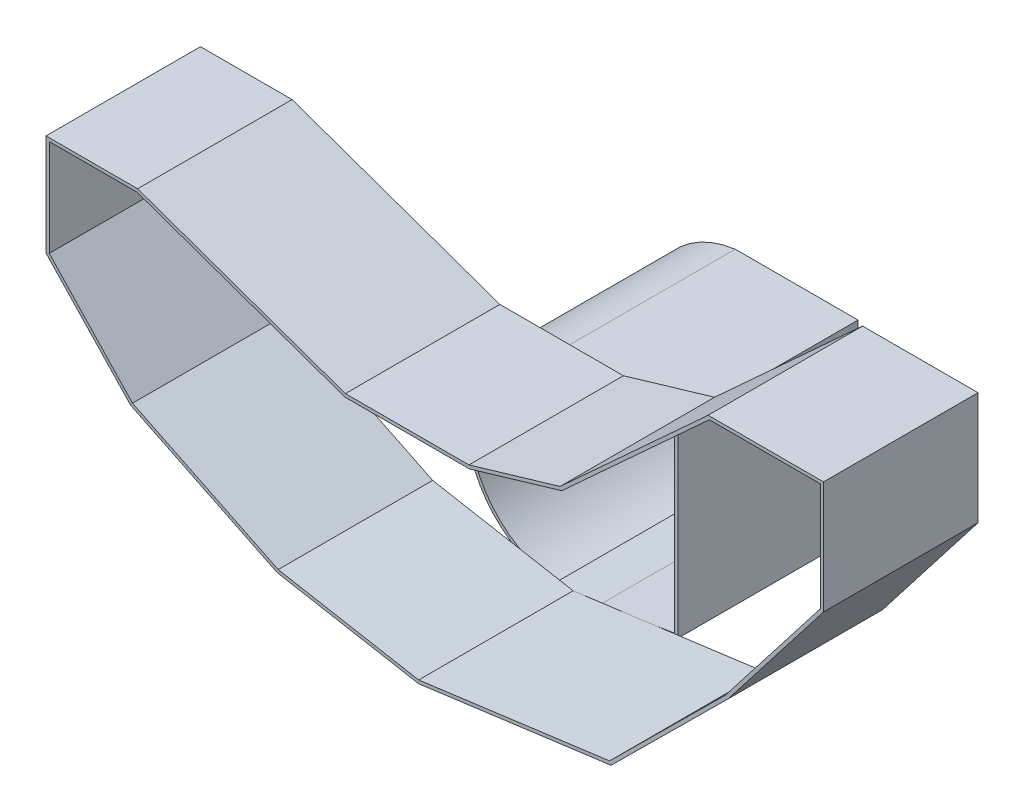
SolidWorks part; units mm, degrees
ref_plane "Front Plane" through (0, 0, 0) normal (0, 0, 1) x (1, 0, 0)
ref_plane "Top Plane" through (0, 0, 0) normal (0, 1, 0) x (1, 0, 0)
ref_plane "Right Plane" through (0, 0, 0) normal (1, 0, 0) x (0, 0, -1)
sketch "Sketch1" plane through (0, 0, 0) normal (0, 0, 1) x (1, 0, 0)
  line L0 (0, 0) -> (0, -75.438)
  line L1 (0, -75.438) -> (149.098, -55.626)
  line L2 (149.098, -55.626) -> (239.776, 34.29)
  line L3 (239.776, 34.29) -> (313.69, 129.54)
  line L4 (313.69, 129.54) -> (313.69, 214.122)
  line L5 (313.69, 214.122) -> (227.076, 214.122)
  line L10 (-219.964, 144.526) -> (-288.544, 144.526)
  line L11 (-288.544, 144.526) -> (-288.544, 68.834)
  line L12 (-288.544, 68.834) -> (-223.52, 0)
  line L15 (-223.52, 0) -> (-109.728, -55.626)
  line L16 (-109.728, -55.626) -> (0, -75.438)
  line L17 (-219.964, 144.526) -> (-57.658, 87.122)
  line L18 (-57.658, 87.122) -> (39.624, 87.122)
  line L20 (111.76, 108.458) -> (227.076, 214.122)
  line L22 (-219.5281, 147.066) -> (-57.2221, 89.662)
  line L23 (-57.2221, 89.662) -> (39.2562, 89.662)
  line L24 (39.2562, 89.662) -> (110.4768, 110.7272)
  line L25 (110.4768, 110.7272) -> (226.0883, 216.662)
  line L26 (226.0883, 216.662) -> (316.23, 216.662)
  line L27 (316.23, 216.662) -> (316.23, 128.6701)
  line L28 (316.23, 128.6701) -> (241.6816, 32.6025)
  line L29 (241.6816, 32.6025) -> (150.2797, -58.0313)
  line L30 (150.2797, -58.0313) -> (-0.0598, -78.0083)
  line L31 (-0.0598, -78.0083) -> (-110.5265, -58.0629)
  line L32 (-110.5265, -58.0629) -> (-225.0498, -2.0794)
  line L33 (-225.0498, -2.0794) -> (-291.084, 67.824)
  line L34 (-291.084, 67.824) -> (-291.084, 147.066)
  line L35 (-291.084, 147.066) -> (-219.5281, 147.066)
  line L36 (111.76, 108.458) -> (39.624, 87.122)
  point P3 (-223.52, 0)
  point P4 (-109.728, -55.626)
  point P5 (-288.544, 68.834)
  point P6 (149.098, -55.626)
  point P7 (239.776, 34.29)
  point P8 (313.69, 129.54)
  point P9 (313.69, 214.122)
  point P10 (-288.544, 144.526)
  point P11 (-219.964, 144.526)
  point P12 (-155.194, 113.792)
  point P13 (-57.658, 87.122)
  point P14 (39.624, 87.122)
  point P15 (111.76, 108.458)
  point P16 (227.076, 214.122)
  dimension "D1" = 75.438
  dimension "D2" = 149.098
  dimension "D3" = 19.812
  dimension "D4" = 109.728
  dimension "D5" = 223.52
  dimension "D6" = 75.438
  dimension "D7" = 602.234
  dimension "D8" = 144.272
  dimension "D9" = 239.776
  dimension "D10" = 109.728
  dimension "D11" = 313.69
  dimension "D12" = 204.978
  dimension "D13" = 289.56
  dimension "D14" = 219.964
  dimension "D15" = 68.58
  dimension "D16" = 133.35
  dimension "D17" = 189.23
  dimension "D18" = 230.886
  dimension "D19" = 162.56
  dimension "D21" = 328.168
  dimension "D22" = 400.304
  dimension "D23" = 515.62
  dimension "D24" = 19.812
  dimension "D25" = 183.896
  dimension "D26" = 2.54
  dimension "D27" = 2.54
  dimension "D28" = 2.54
  dimension "D29" = 2.54
  dimension "D30" = 2.54
  dimension "D31" = 2.54
  dimension "D32" = 2.54
  dimension "D33" = 2.54
  dimension "D34" = 2.54
  dimension "D35" = 2.54
  dimension "D36" = 2.54
  dimension "D37" = 2.54
  dimension "D38" = 2.54
  dimension "D39" = 2.54
extrude "Boss-Extrude1" add sketch "Sketch1" against normal blind 120.65 contours L35 L34 L33 L32 L31 L30 L29 L28 L27 L26 L25 L24 L23 L22 L36 L20 L5 L4 L3 L2 L1 L16 L15 L12 L11 L10 L17 L18
sketch "Sketch2" plane through (0, 0, -120.65) normal (0, 0, -1) x (-1, 0, 0)
  line L0 (-79.248, 75.692) -> (-79.248, -64.516)
  line L1 (-79.248, 75.692) -> (12.4956, 75.692)
  line L2 (-79.248, -64.516) -> (-21.59, -73.66)
  line L3 (-21.59, -73.66) -> (14.224, -77.216)
  line L4 (-81.788, 78.232) -> (14.0982, 78.232)
  line L5 (-81.788, 78.232) -> (-81.788, -66.6849)
  line L6 (-81.788, -66.6849) -> (-21.9147, -76.1803)
  line L7 (-21.9147, -76.1803) -> (14.0982, -79.756)
  arc A0 (14.224, -77.216) -> (12.4956, 75.692) centre (3.7116, -0.8711) ccw
  arc A1 (14.0982, -79.756) -> (14.0982, 78.232) centre (3.627, -0.762) ccw
  point P0 (0, 0)
  point P4 (-102.87, 88.138)
  point P5 (80.772, 0)
  point P6 (14.224, -77.216)
  point P17 (83.312, -0.762)
  point P23 (-21.59, -73.66)
  dimension "D1" = 79.248
  dimension "D2" = 88.138
  dimension "D3" = 102.87
  dimension "D4" = 160.02
  dimension "D5" = 77.216
  dimension "D6" = 93.472
  dimension "D7" = 88.138
  dimension "D8" = 12.7
  dimension "D9" = 152.908
  dimension "D10" = 149.352
  dimension "D11" = 57.658
  dimension "D12" = 2.54
  dimension "D13" = 2.54
  dimension "D14" = 2.54
  dimension "D15" = 2.54
  dimension "D16" = 2.54
  dimension "D17" = 2.54
extrude "Boss-Extrude2" add sketch "Sketch2" along normal blind 140.716
sketch "Sketch3" plane through (0, 0, 0) normal (0, 0, 1) x (1, 0, 0)
  circle A2 centre (0, 0) radius 39.116
  circle A3 centre (57.2357, 15.0526) radius 20.066
  circle A4 centre (114.8817, 22.8133) radius 38.1
  circle A5 centre (114.8817, 22.8133) radius 23.622
  circle A6 centre (160.02, 57.658) radius 33.401
  circle A7 centre (0, 0) radius 50.8
  circle A8 centre (-94.9639, -7.3764) radius 15.875
  circle A9 centre (-94.9639, -7.3764) radius 44.45
  circle A10 centre (-145.542, 36.068) radius 50.8
  circle A11 centre (160.02, 57.658) radius 41.275
  circle A12 centre (201.1776, 97.3086) radius 15.875
  circle A14 centre (201.5204, 138.5822) radius 25.4
  circle A15 centre (255.27, 152.908) radius 30.226
  circle A16 centre (-145.542, 36.068) radius 35.56
  circle A17 centre (-184.5582, 81.2414) radius 24.13
  circle A18 centre (-184.5582, 81.2414) radius 35.56
  circle A19 centre (-241.046, 89.916) radius 21.59
  circle A20 centre (201.5204, 138.5822) radius 25.4
  point P0 (-145.542, 36.068)
  point P30 (0, 0)
  point P32 (0, 0)
  point P33 (0, 0)
  point P34 (160.02, 57.658)
  point P35 (-80.5301, 50.8671)
  point P36 (-96.3892, -8.9826)
  point P37 (-241.046, 89.916)
  point P38 (114.8817, 22.8133)
  point P48 (255.27, 152.908)
  dimension "D3" = 71.12
  dimension "D4" = 78.232
  dimension "D5" = 40.132
  dimension "D6" = 76.2
  dimension "D7" = 47.244
  dimension "D8" = 66.802
  dimension "D9" = 101.6
  dimension "D10" = 31.75
  dimension "D11" = 88.9
  dimension "D12" = 101.6
  dimension "D13" = 82.55
  dimension "D14" = 31.75
  dimension "D15" = 50.8
  dimension "D16" = 60.452
  dimension "D17" = 48.26
  dimension "D18" = 71.12
  dimension "D19" = 43.18
  dimension "D20" = 160.02
  dimension "D24" = 50.8
  dimension "D1" = 145.542
  dimension "D2" = 36.068
  dimension "D21" = 255.27
  dimension "D22" = 57.658
  dimension "D23" = 152.908
  dimension "D25" = 241.046
  dimension "D26" = 89.916
sketch "Sketch4" plane through (0, 0, -120.65) normal (0, 0, 1) x (1, 0, 0)
  circle A0 centre (0, -0.6467) radius 0.6467
  circle A1 centre (0, -0.6467) radius 44.45
  dimension "D1" = 88.9
